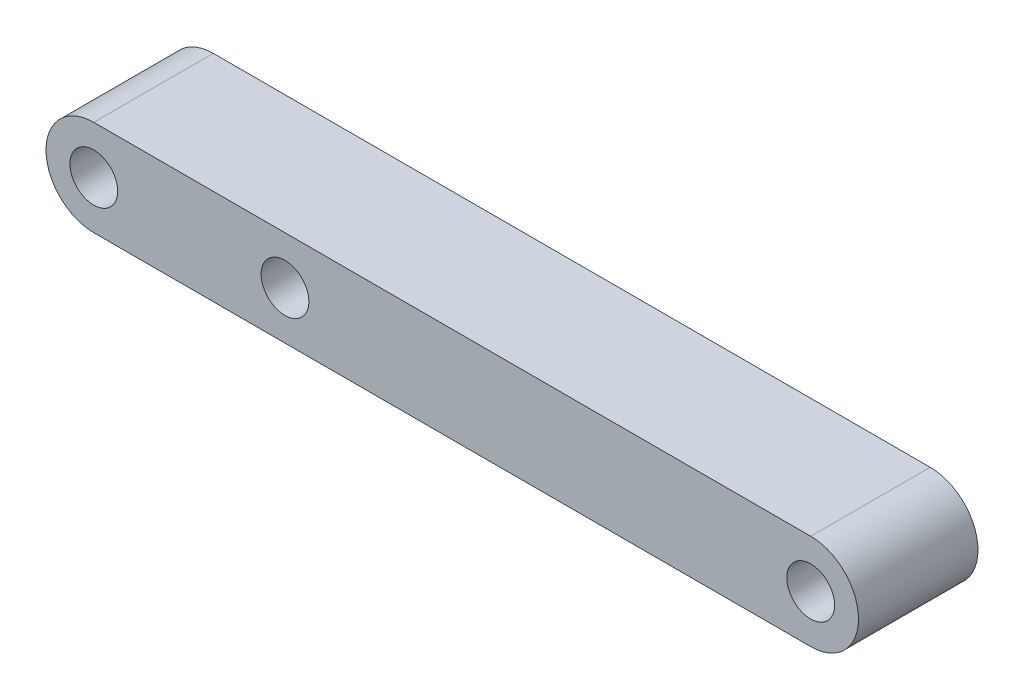
SolidWorks part; units mm, degrees
material "AISI 1020"
ref_plane "Plan de face" through (0, 0, 0) normal (0, 0, 1) x (1, 0, 0)
ref_plane "Plan de dessus" through (0, 0, 0) normal (0, 1, 0) x (1, 0, 0)
ref_plane "Plan de droite" through (0, 0, 0) normal (1, 0, 0) x (0, 0, -1)
sketch "Esquisse1" plane through (0, 0, 0) normal (0, 0, 1) x (1, 0, 0)
  line L0 (0, 0) -> (60, 0) construction
  line L1 (0, 4) -> (60, 4)
  line L2 (0, -4) -> (60, -4)
  arc A0 (0, 4) -> (0, -4) centre (0, 0) ccw
  arc A1 (60, -4) -> (60, 4) centre (60, 0) ccw
  circle A2 centre (0, 0) radius 2
  circle A3 centre (60, 0) radius 2
  circle A5 centre (16, 0) radius 2
  point P3 (30, 0)
  dimension "D2" = 4
  dimension "D3" = 4
  dimension "D4" = 16
  dimension "D1" = 60
extrude "Boss.-Extru.1" add sketch "Esquisse1" along normal blind 10
